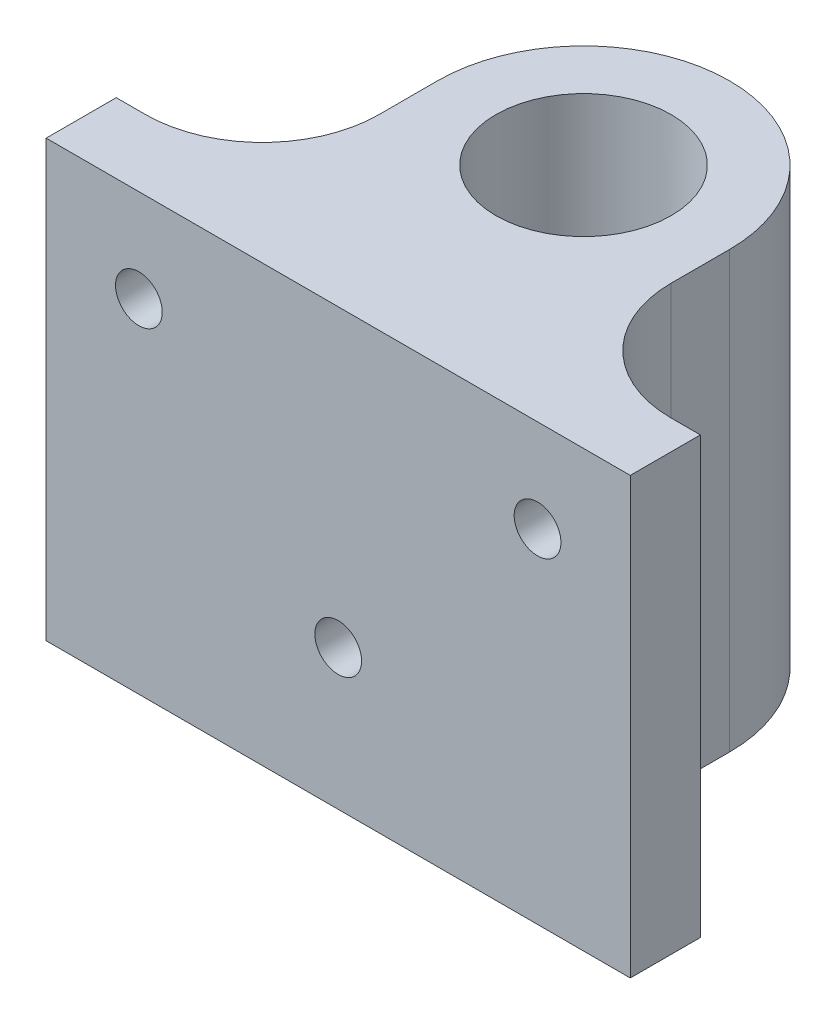
SolidWorks part; units mm, degrees
ref_plane "Front Plane" through (0, 0, 0) normal (0, 0, 1) x (1, 0, 0)
ref_plane "Top Plane" through (0, 0, 0) normal (0, 1, 0) x (1, 0, 0)
ref_plane "Right Plane" through (0, 0, 0) normal (1, 0, 0) x (0, 0, -1)
sketch "Profile-Sketch1" plane through (0, 0, 0) normal (0, 1, 0) x (1, 0, 0)
  line L0 (-25, -21) -> (25, -21)
  line L1 (25, -21) -> (25, -15)
  line L2 (-25, -21) -> (-25, -15)
  line L3 (-25, -15) -> (-22.5, -15)
  line L4 (-12.5, -5) -> (-12.5, 0)
  line L5 (25, -15) -> (22.5, -15)
  line L6 (12.5, -5) -> (12.5, 0)
  circle A0 centre (0, 0) radius 7.5
  arc A6 (12.5, 0) -> (-12.5, 0) centre (0, 0) ccw
  arc A7 (22.5, -15) -> (12.5, -5) centre (22.5, -5) cw
  arc A8 (-12.5, -5) -> (-22.5, -15) centre (-22.5, -5) cw
  dimension "D1" = 15
  dimension "D2" = 12.5
  dimension "D7" = 10
  dimension "D3" = 50
  dimension "D4" = 25
  dimension "D5" = 21
  dimension "D6" = 6
extrude "Profile-Boss-Extrude2" add sketch "Profile-Sketch1" along normal blind 37.2599
sketch "FasteningHoleSketch3" plane through (0, 0, 21) normal (0, 0, 1) x (1, 0, 0)
  line L0 (25, 37.2599) -> (25, 0) construction
  line L1 (-25, 37.2599) -> (-25, 0) construction
  line L2 (-25, 0) -> (25, 0) construction
  circle A2 centre (-17.0625, 29.3224) radius 2
  circle A3 centre (17.0625, 29.3224) radius 2
  dimension "D3" = 4
  dimension "D6" = 7.9375
  dimension "D2" = 29.3224
  dimension "D1" = 7.9375
extrude "FasteningHoleCut-Extrude8" cut sketch "FasteningHoleSketch3" against normal through all
sketch "LM8UUFasteningHoleSketch5" plane through (0, 0, 21) normal (0, 0, 1) x (1, 0, 0)
  line L0 (25, 37.2599) -> (25, 0) construction
  line L1 (-25, 0) -> (25, 0) construction
  line L2 (-25, 37.2599) -> (25, 37.2599) construction
  circle A0 centre (0, 12) radius 2
  circle A1 centre (-17.0625, 29.3224) radius 2 construction
  dimension "D1" = 25
  dimension "D2" = 12
  dimension "D3" = 25.2599
extrude "LM8UUFasteningHoleCut-Extrude9" cut sketch "LM8UUFasteningHoleSketch5" against normal through all
equation "\"RailThickness\"= .125in'Spec"
equation "\"LM8UUDiameter\"= 15mm"
equation "\"MidLeftOrRightSideRailHeight\"= 2.0in"
equation "\"RodStabilizerLength\"= 50mm"
equation "\"HoleOffsetFromEdge\"= \"RailThickness\" * 2.5"
equation "\"StepperMountingHoleOffsetFromItsSide\"= 5.5mm'Spec"
equation "\"StepperMountingHoleOffsetFromLeftOrRightSide\"= \"StepperMountingHoleOffsetFromItsSide\" + \"RailThickness\""
equation "\"StepperMountingHoleDistance\"= 31mm'Spec"
equation "\"LM8UUHeight\"= 24mm'Spec"
equation "\"ZAxisLeadScrewLength\"= 200mm"
equation "\"LegHeight\"= 70mm'Space needed for PSU/Stepper/Electronics"
equation "\"V1 BottomOfLowerRail\"= \"LegHeight\""
equation "\"StepperShaftLength\"= 24mm'Pulley will be attached to the end"
equation "\"V2 ToBedAtTopOfZAxis\"= \"V1 BottomOfLowerRail\" - \"LowerEnclosureThickness\" + \"StepperShaftLength\" + \"ZAxisLeadScrewLength\" - \"LM8UUHeight\" / 2'Equals 277"
equation "\"HotEndToTopOfXAxisGB\"= 71.68487'Equals 71.68487mm.  Measured after install onto X-Axis linear rail guide block"
equation "\"TopOfGBToBottomOfLinearRail\"= \"LinearGBWidth\" / 2 + \"LinearRailWidth\" / 2'Equals 19.5"
equation "\"LinearGBWidth\"= 27mm'Spec"
equation "\"V5 ToBottomOfXAxisLinearRail\"= \"V4 ToTopOfBuildPlate/HotEndTip\" + \"HotEndToTopOfXAxisGB\" - \"TopOfGBToBottomOfLinearRail\"'Equals 352.18487"
equation "\"LinearRailWidth\"= 12mm'Spec"
equation "\"V6 ToMiddleOfYAxisGantryBlock\"= \"V5 ToBottomOfXAxisLinearRail\" - \"GABHeight\" / 2'Equals 334.18487"
equation "\"GABUpperHeight\" = 4mm"
equation "\"GABMidWallHeight\"= 28mm'Must equal 28 or changes alignment"
equation "\"BedToBuildPlateStandoffLength\"= 15mm"
equation "\"BuildPlateHeight\"= 8mm'Spec"
equation "\"V4 ToTopOfBuildPlate/HotEndTip\"= \"V2 ToBedAtTopOfZAxis\" + \"BedToBuildPlateStandoffLength\" + \"BuildPlateHeight\""
equation "\"RodStabilizerHeight\"= \"V8 ToBottomOfMidSideRail\" - \"V2 ToBedAtTopOfZAxis\" + \"HoleOffsetFromEdge\" * 2"
equation "\"LowerEnclosureThickness\"= 5mm"
equation "\"D1@Profile-Sketch1\" = \"LM8UUDiameter\""
equation "\"D3@Profile-Sketch1\" = \"RodStabilizerLength\""
equation "\"D4@Profile-Sketch1\" = \"RodStabilizerLength\" / 2"
equation "\"RodStabilizerWidthFromMidRailToZAxisRodCenter\"= \"StepperMountingHoleOffsetFromLeftOrRightSide\" + \"StepperMountingHoleDistance\" / 2 - \"RailThickness\""
equation "\"StandardWallThickness\"= 3mm"
equation "\"D6@Profile-Sketch1\" = \"StandardWallThickness\" * 2"
equation "\"D1@Profile-Boss-Extrude2\"= \"RodStabilizerHeight\""
equation "\"D6@FasteningHoleSketch3\"=\"HoleOffsetFromEdge\""
equation "\"D2@LM8UUFasteningHoleSketch5\"=\"LM8UUHeight\"/2"
equation "\"V8 ToTopOfMidSideRail\"= \"V6 ToMiddleOfYAxisGantryBlock\" + \"MidSideRailVerticalOffset\"'Equals 349.18487"
equation "\"D5@Profile-Sketch1\"=\"RodStabilizerWidthFromMidRailToZAxisRodCenter\""
equation "\"RodStabilizerMountingHoleYOffsetFromBottom\"= \"RodStabilizerHeight\" - \"HoleOffsetFromEdge\""
equation "\"D2@FasteningHoleSketch3\"=\"RodStabilizerMountingHoleYOffsetFromBottom\""
equation "\"D3@FasteningHoleSketch3\"=\"M3HeatInsertHoleDiameter\""
equation "\"GABLowerHeight\" = 4mm"
equation "\"GABHeight\"= \"GABLowerHeight\" + \"GABMidWallHeight\" + \"GABUpperHeight\""
equation "\"V8 ToBottomOfMidSideRail\"= \"V8 ToTopOfMidSideRail\" - \"MidLeftOrRightSideRailHeight\"'Equals 298.38487"
equation "\"D1@LM8UUFasteningHoleSketch5\"=\"RodStabilizerLength\"/2"
equation "\"MidSideRailVerticalOffset\"= \"LinearRailWidth\" + 3mm'Allows space for RodStabilizer to attach to bottom of MidSideRail"
equation "\"M3HeatInsertHoleDiameter\"= 4mm'Spec"
